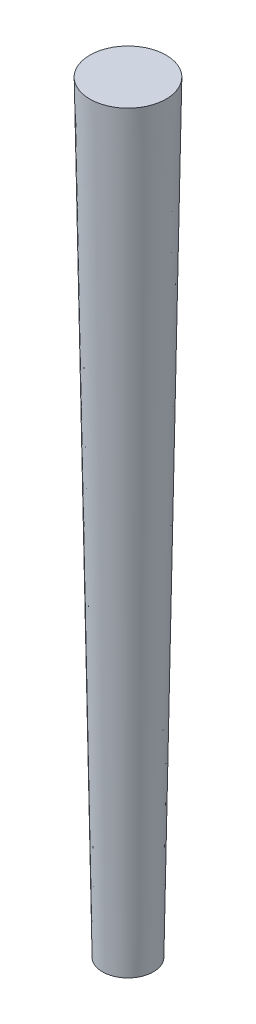
SolidWorks part; units mm, degrees
ref_plane "Front Plane" through (0, 0, 0) normal (0, 0, 1) x (1, 0, 0)
ref_plane "Top Plane" through (0, 0, 0) normal (0, 1, 0) x (1, 0, 0)
ref_plane "Right Plane" through (0, 0, 0) normal (1, 0, 0) x (0, 0, -1)
sketch "Sketch1" plane through (0, 0, 0) normal (0, 0, 1) x (1, 0, 0)
  line L0 (0, 0) -> (2, 0)
  line L1 (2, 0) -> (3, 60)
  line L2 (3, 60) -> (0, 60)
  line L3 (0, 60) -> (0, 0)
  dimension "D1" = 3
  dimension "D2" = 2
  dimension "D3" = 60
revolve "Revolve1" add sketch "Sketch1" angle 360 about L3
